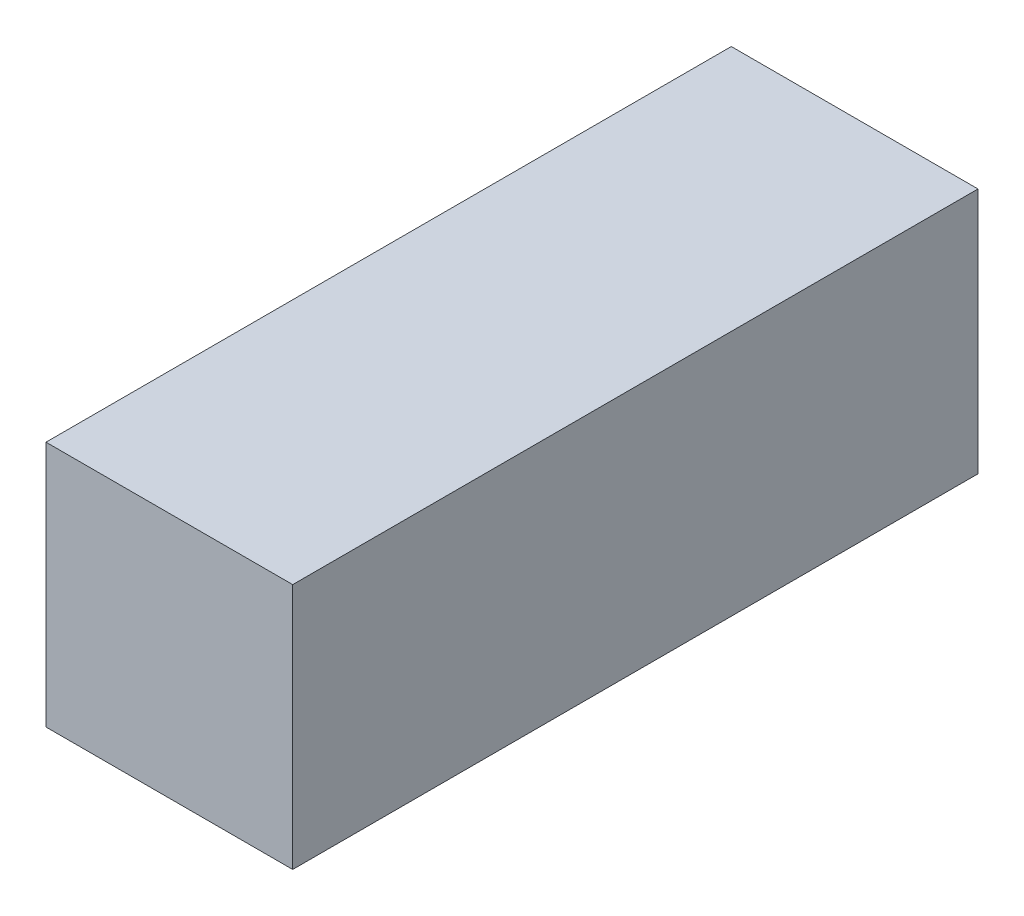
SolidWorks part; units mm, degrees
material "AISI 4340 Steel, annealed"
ref_plane "Front Plane" through (0, 0, 0) normal (0, 0, 1) x (1, 0, 0)
ref_plane "Top Plane" through (0, 0, 0) normal (0, 1, 0) x (1, 0, 0)
ref_plane "Right Plane" through (0, 0, 0) normal (1, 0, 0) x (0, 0, -1)
sketch "Sketch1" plane through (0, 0, 0) normal (0, 0, 1) x (1, 0, 0)
  line L1 (-18, -18) -> (18, -18)
  line L2 (-18, -18) -> (-18, 18)
  line L3 (-18, 18) -> (18, 18)
  line L4 (18, -18) -> (18, 18)
  line L5 (-18, -18) -> (18, 18) construction
  line L6 (-18, 18) -> (18, -18) construction
  point P0 (0, 0)
  dimension "D1" = 36
extrude "Boss-Extrude1" add sketch "Sketch1" against normal blind 100
